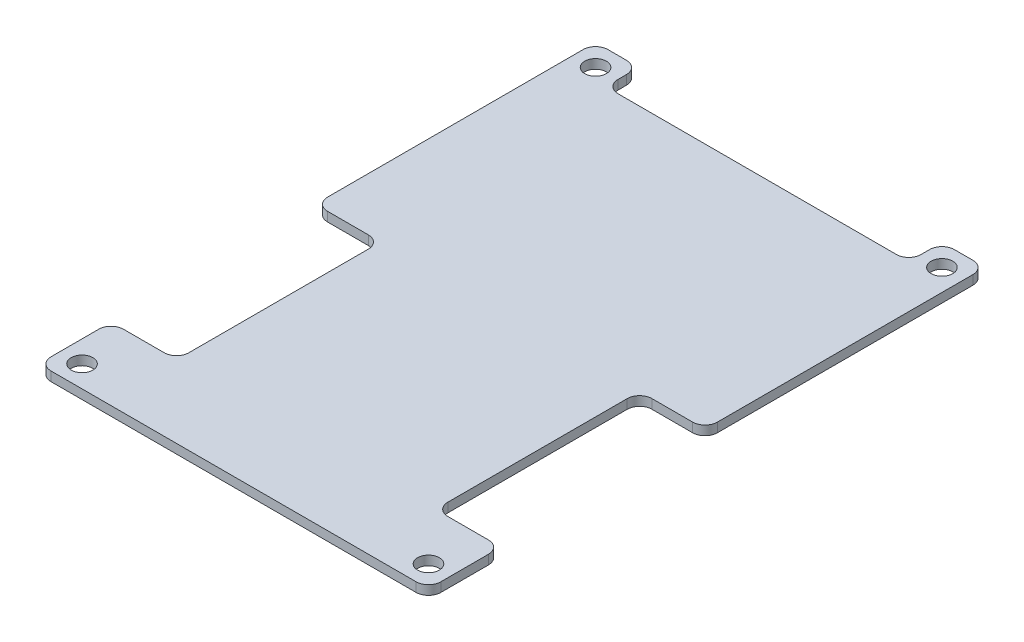
SolidWorks part; units mm, degrees
material "AISI 304"
ref_plane "Front Plane" through (0, 0, 0) normal (0, 0, 1) x (1, 0, 0)
ref_plane "Top Plane" through (0, 0, 0) normal (0, 1, 0) x (1, 0, 0)
ref_plane "Right Plane" through (0, 0, 0) normal (1, 0, 0) x (0, 0, -1)
sketch "Sketch1" plane through (0, 0, 0) normal (0, 1, 0) x (1, 0, 0)
  line L0 (0, 51.2647) -> (0, -60.5294) construction
  line L1 (-51.6765, 0) -> (94.0882, 0) construction
  line L2 (29.5, -0.3) -> (22.925, -0.3)
  line L3 (29.5, -45) -> (-29.5, -45)
  line L4 (31.5, -43) -> (31.5, -35.3)
  line L5 (29.5, 45) -> (26.5, 45)
  line L6 (-31.5, -43) -> (-31.5, -35.3)
  line L7 (31.5, -45) -> (-31.5, 45) construction
  line L8 (31.5, 45) -> (-31.5, -45) construction
  line L9 (20.925, -2.3) -> (20.925, -31.3)
  line L10 (22.925, -33.3) -> (29.5, -33.3)
  line L11 (31.5, 1.7) -> (31.5, 43)
  line L12 (-20.925, -2.3) -> (-20.925, -31.3)
  line L13 (-22.925, -0.3) -> (-29.5, -0.3)
  line L14 (-22.925, -33.3) -> (-29.5, -33.3)
  line L15 (-31.5, 1.7) -> (-31.5, 43)
  line L16 (-24.5, 43) -> (-24.5, 41.631)
  line L17 (-22.5, 39.631) -> (22.5, 39.631)
  line L18 (24.5, 43) -> (24.5, 41.631)
  line L19 (-26.5, 45) -> (-29.5, 45)
  arc A0 (29.5, -33.3) -> (31.5, -35.3) centre (29.5, -35.3) cw
  arc A1 (31.5, -43) -> (29.5, -45) centre (29.5, -43) cw
  arc A2 (-31.5, -43) -> (-29.5, -45) centre (-29.5, -43) ccw
  arc A3 (-29.5, -33.3) -> (-31.5, -35.3) centre (-29.5, -35.3) ccw
  arc A4 (-20.925, -31.3) -> (-22.925, -33.3) centre (-22.925, -31.3) cw
  arc A5 (20.925, -31.3) -> (22.925, -33.3) centre (22.925, -31.3) ccw
  arc A6 (31.5, 1.7) -> (29.5, -0.3) centre (29.5, 1.7) cw
  arc A7 (22.925, -0.3) -> (20.925, -2.3) centre (22.925, -2.3) ccw
  arc A8 (-20.925, -2.3) -> (-22.925, -0.3) centre (-22.925, -2.3) ccw
  arc A9 (-29.5, -0.3) -> (-31.5, 1.7) centre (-29.5, 1.7) cw
  arc A10 (-29.5, 45) -> (-31.5, 43) centre (-29.5, 43) ccw
  arc A11 (-26.5, 45) -> (-24.5, 43) centre (-26.5, 43) cw
  arc A12 (26.5, 45) -> (24.5, 43) centre (26.5, 43) ccw
  arc A13 (31.5, 43) -> (29.5, 45) centre (29.5, 43) ccw
  arc A14 (24.5, 41.631) -> (22.5, 39.631) centre (22.5, 41.631) cw
  arc A15 (-24.5, 41.631) -> (-22.5, 39.631) centre (-22.5, 41.631) ccw
  circle A16 centre (27.9963, 41.5) radius 1.75
  circle A17 centre (-27.9963, 41.5) radius 1.75
  circle A19 centre (28, -41.5) radius 1.75
  circle A20 centre (-28, -41.5) radius 1.75
  point P5 (0, 0)
  point P34 (-20.925, -33.3)
  point P37 (20.925, -33.3)
  point P40 (31.5, -0.3)
  point P43 (20.925, -0.3)
  point P46 (-20.925, -0.3)
  point P49 (-31.5, -0.3)
  point P55 (-24.5, 45)
  point P58 (24.5, 45)
  point P64 (24.5, 39.631)
  point P67 (-24.5, 39.631)
  dimension "D7" = 2
  dimension "D8" = 2
  dimension "D9" = 3.5
  dimension "D13" = 3.5
  dimension "D1" = 63
  dimension "D2" = 45.3
  dimension "D3" = 33
  dimension "D4" = 90
  dimension "D5" = 41.85
  dimension "D6" = 7
  dimension "D10" = 3.5
  dimension "D11" = 3.5
  dimension "D12" = 3.5
extrude "Boss-Extrude1" add sketch "Sketch1" along normal mid plane 1.5
